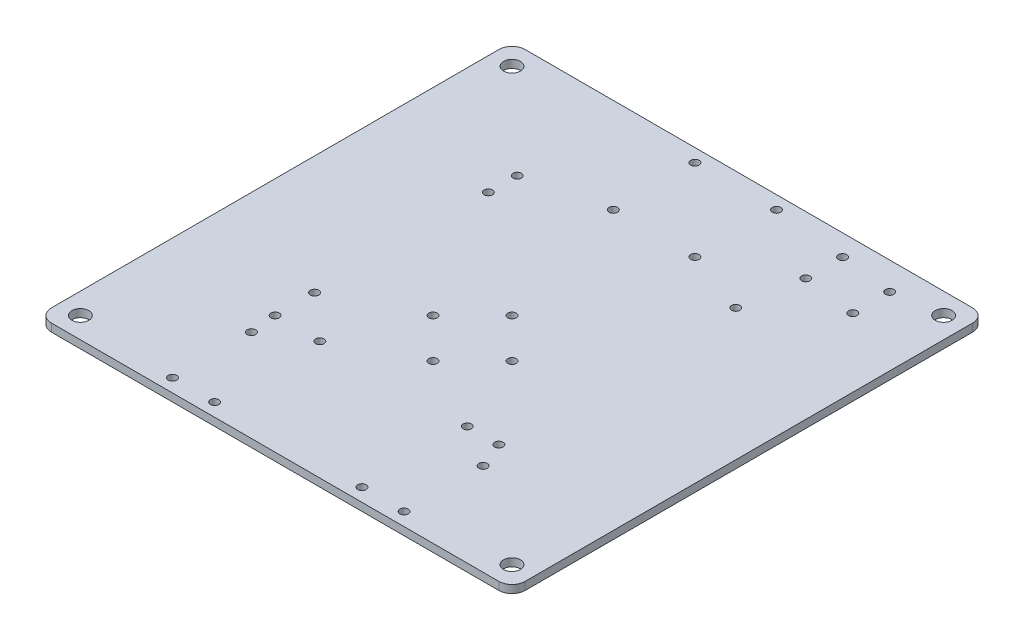
SolidWorks part; units mm, degrees
ref_plane "前视基准面" through (0, 0, 0) normal (0, 0, 1) x (1, 0, 0)
ref_plane "上视基准面" through (0, 0, 0) normal (0, 1, 0) x (1, 0, 0)
ref_plane "右视基准面" through (0, 0, 0) normal (1, 0, 0) x (0, 0, -1)
sketch "草图1" plane through (0, 0, 0) normal (0, 1, 0) x (1, 0, 0)
  line L0 (90, 130) -> (90, -20) construction
  line L1 (5, 0) -> (175, 0)
  line L2 (0, 5) -> (0, 175)
  line L3 (5, 180) -> (175, 180)
  line L4 (180, 5) -> (180, 175)
  line L5 (0, 90) -> (150, 90) construction
  arc A0 (0, 175) -> (5, 180) centre (5, 175) cw
  arc A1 (5, 0) -> (0, 5) centre (5, 5) cw
  arc A2 (175, 0) -> (180, 5) centre (175, 5) ccw
  arc A3 (175, 180) -> (180, 175) centre (175, 175) cw
  circle A4 centre (8, 172) radius 3.2
  circle A5 centre (172, 172) radius 3.2
  circle A6 centre (8, 8) radius 3.2
  circle A7 centre (172, 8) radius 3.2
  circle A8 centre (74.5, 175) radius 1.6
  circle A9 centre (74.5, 144) radius 1.6
  circle A10 centre (105.5, 144) radius 1.6
  circle A11 centre (105.5, 175) radius 1.6
  circle A12 centre (133.6, 172) radius 1.6
  circle A13 centre (133.6, 158) radius 1.6
  circle A14 centre (154, 169.5) radius 1.6
  circle A15 centre (154, 155.5) radius 1.6
  circle A16 centre (130, 135) radius 1.6
  circle A17 centre (130, 45) radius 1.6
  circle A18 centre (45, 137) radius 1.6
  circle A19 centre (45, 45) radius 1.6
  circle A20 centre (45, 126) radius 1.6
  circle A21 centre (45, 60) radius 1.6
  circle A22 centre (62, 45) radius 1.6
  circle A23 centre (62, 5) radius 1.6
  circle A24 centre (118, 45) radius 1.6
  circle A25 centre (118, 5) radius 1.6
  circle A26 centre (90, 90) radius 1.6
  circle A27 centre (90, 60) radius 1.6
  circle A30 centre (105, 75) radius 1.6
  circle A31 centre (75, 75) radius 1.6
  circle A32 centre (46, 5) radius 1.6
  circle A33 centre (46, 35) radius 1.6
  circle A34 centre (134, 35) radius 1.6
  circle A35 centre (134, 5) radius 1.6
  point P9 (0, 0)
  point P12 (180, 0)
  point P15 (180, 180)
  point P64 (90, 180)
  point P65 (0, 90)
  dimension "D3" = 5
  dimension "D4" = 8
  dimension "D12" = 31
  dimension "D15" = 14
  dimension "D21" = 90
  dimension "D24" = 92
  dimension "D27" = 66
  dimension "D30" = 56
  dimension "D37" = 30
  dimension "D38" = 15
  dimension "D42" = 88
  dimension "D1" = 180
  dimension "D2" = 180
  dimension "D5" = 8
  dimension "D6" = 8
  dimension "D7" = 8
  dimension "D8" = 8
  dimension "D9" = 8
  dimension "D10" = 8
  dimension "D11" = 8
  dimension "D13" = 5
  dimension "D14" = 15.5
  dimension "D16" = 14
  dimension "D17" = 2.5
  dimension "D18" = 20.4
  dimension "D19" = 26
  dimension "D20" = 8
  dimension "D22" = 45
  dimension "D23" = 50
  dimension "D25" = 45
  dimension "D26" = 45
  dimension "D28" = 60
  dimension "D29" = 45
  dimension "D31" = 56
  dimension "D32" = 40
  dimension "D33" = 28
  dimension "D34" = 0
  dimension "D35" = 0
  dimension "D36" = 5
  dimension "D39" = 15
  dimension "D40" = 15
  dimension "D41" = 15
  dimension "D43" = 44
  dimension "D44" = 5
  dimension "D45" = 5
  dimension "D46" = 44
  dimension "D47" = 44
  dimension "D48" = 30
  dimension "D49" = 35
  dimension "D50" = 28
  dimension "D51" = 0
extrude "凸台-拉伸1" add sketch "草图1" along normal blind 3
